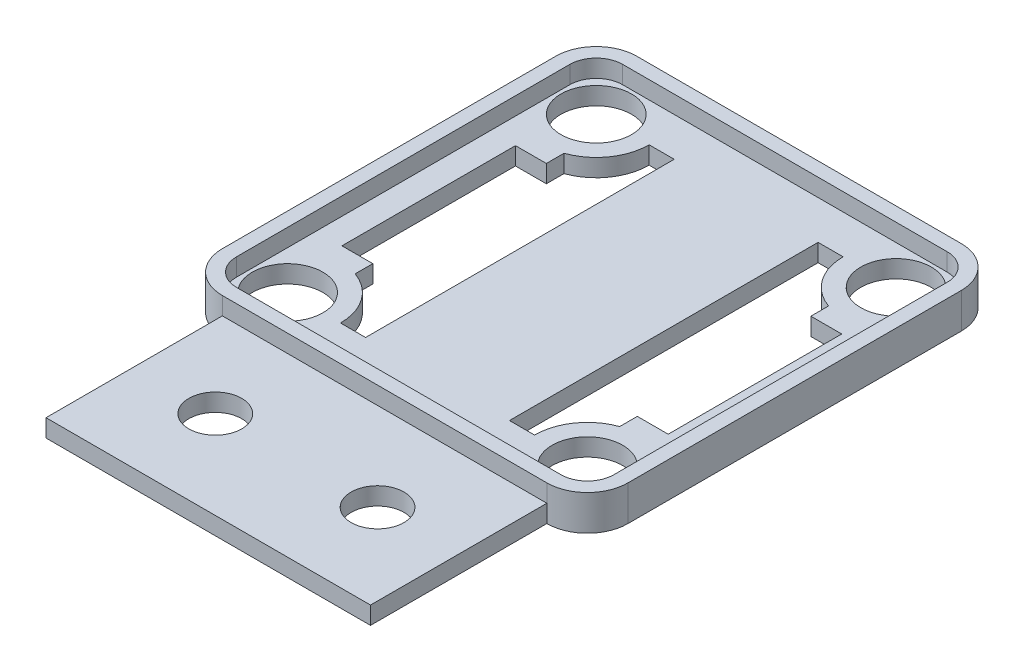
SolidWorks part; units mm, degrees
ref_plane "Front Plane" through (0, 0, 0) normal (0, 0, 1) x (1, 0, 0)
ref_plane "Top Plane" through (0, 0, 0) normal (0, 1, 0) x (1, 0, 0)
ref_plane "Right Plane" through (0, 0, 0) normal (1, 0, 0) x (0, 0, -1)
sketch "Sketch1" plane through (0, 0, 0) normal (0, 1, 0) x (1, 0, 0)
  line L1 (-12.6491, 14.6331) -> (5.7509, 14.6331)
  line L2 (-14.9491, 12.3331) -> (-14.9491, -6.5669)
  line L3 (-12.6491, -8.8669) -> (5.7509, -8.8669)
  line L4 (8.0509, 12.3331) -> (8.0509, -6.5669)
  line L5 (-14.9491, 14.6331) -> (8.0509, -8.8669) construction
  line L6 (-14.9491, -8.8669) -> (8.0509, 14.6331) construction
  arc A0 (8.0509, 12.3331) -> (5.7509, 14.6331) centre (5.7509, 12.3331) ccw
  arc A1 (-12.6491, -8.8669) -> (-14.9491, -6.5669) centre (-12.6491, -6.5669) cw
  arc A2 (5.7509, -8.8669) -> (8.0509, -6.5669) centre (5.7509, -6.5669) ccw
  arc A3 (-14.9491, 12.3331) -> (-12.6491, 14.6331) centre (-12.6491, 12.3331) cw
  point P0 (-3.4491, 2.8831)
  dimension "D3" = 2.3
  dimension "D4" = 2.3
  dimension "D1" = 23.5
  dimension "D2" = 23
extrude "Boss-Extrude1" add sketch "Sketch1" along normal blind 2
sketch "Sketch2" plane through (0, 2, 0) normal (0, 1, 0) x (1, 0, 0)
  line L8 (5.7509, 13.6331) -> (-12.6491, 13.6331)
  line L9 (-13.9491, 12.3331) -> (-13.9491, -6.5669)
  line L10 (-12.6491, -7.8669) -> (5.7509, -7.8669)
  line L11 (7.0509, -6.5669) -> (7.0509, 12.3331)
  line L12 (5.7509, 13.6331) -> (-12.6491, 13.6331)
  line L13 (-13.9491, 12.3331) -> (-13.9491, -6.5669)
  line L14 (-12.6491, -7.8669) -> (5.7509, -7.8669)
  line L15 (7.0509, -6.5669) -> (7.0509, 12.3331)
  arc A8 (7.0509, 12.3331) -> (5.7509, 13.6331) centre (5.7509, 12.3331) ccw
  arc A9 (-12.6491, 13.6331) -> (-13.9491, 12.3331) centre (-12.6491, 12.3331) ccw
  arc A10 (-13.9491, -6.5669) -> (-12.6491, -7.8669) centre (-12.6491, -6.5669) ccw
  arc A11 (5.7509, -7.8669) -> (7.0509, -6.5669) centre (5.7509, -6.5669) ccw
  arc A12 (7.0509, 12.3331) -> (5.7509, 13.6331) centre (5.7509, 12.3331) ccw
  arc A13 (-12.6491, 13.6331) -> (-13.9491, 12.3331) centre (-12.6491, 12.3331) ccw
  arc A14 (-13.9491, -6.5669) -> (-12.6491, -7.8669) centre (-12.6491, -6.5669) ccw
  arc A15 (5.7509, -7.8669) -> (7.0509, -6.5669) centre (5.7509, -6.5669) ccw
  dimension "D1" = 1
extrude "Cut-Extrude2" cut sketch "Sketch2" against normal blind 1
sketch "Sketch5" plane through (0, 1, 0) normal (0, 1, 0) x (1, 0, 0)
  line L0 (-3.4491, 13.6331) -> (-3.4491, -7.8669) construction
  line L1 (5.7509, 13.6331) -> (-12.6491, 13.6331) construction
  line L2 (-12.6491, -7.8669) -> (5.7509, -7.8669) construction
  line L3 (7.0509, 2.8831) -> (-13.9491, 2.8831) construction
  line L4 (7.0509, -6.5669) -> (7.0509, 12.3331) construction
  line L5 (-13.9491, 12.3331) -> (-13.9491, -6.5669) construction
  circle A0 centre (5.0509, 11.6331) radius 2
  circle A1 centre (5.0509, -5.8669) radius 2
  circle A2 centre (-11.9491, -5.8669) radius 2
  circle A3 centre (-11.9491, 11.6331) radius 2
  dimension "D1" = 4
extrude "Cut-Extrude3" cut sketch "Sketch5" against normal through all
sketch "Sketch6" plane through (0, 1, 0) normal (0, 1, 0) x (1, 0, 0)
  line L0 (-14.9491, 12.3331) -> (-14.9491, -6.5669) construction
  line L1 (8.0509, -6.5669) -> (8.0509, 12.3331) construction
  line L14 (4.0509, -5.8669) -> (4.0509, 11.6331)
  line L15 (4.0509, -3.0385) -> (4.0509, 8.8047)
  line L16 (2.0509, 11.6331) -> (2.0509, -5.8669)
  line L17 (-10.9491, 12.3331) -> (-10.9491, -6.5669)
  line L18 (-10.9491, 8.8047) -> (-10.9491, -3.0385)
  line L19 (-8.9491, 11.6331) -> (-8.9491, -5.8669)
  arc A5 (-11.9491, -8.8669) -> (-14.9491, -5.8669) centre (-11.9491, -5.8669) ccw
  arc A6 (-8.9491, -5.8669) -> (-10.9491, -3.0385) centre (-11.9491, -5.8669) ccw
  arc A20 (5.0509, 14.6331) -> (8.0509, 11.6331) centre (5.0509, 11.6331) ccw
  arc A21 (2.0509, 11.6331) -> (4.0509, 8.8047) centre (5.0509, 11.6331) ccw
  arc A23 (-14.9491, 11.6331) -> (-11.9491, 14.6331) centre (-11.9491, 11.6331) ccw
  arc A24 (-10.9491, 8.8047) -> (-8.9491, 11.6331) centre (-11.9491, 11.6331) ccw
  arc A26 (8.0509, -5.8669) -> (5.0509, -8.8669) centre (5.0509, -5.8669) ccw
  arc A27 (4.0509, -3.0385) -> (2.0509, -5.8669) centre (5.0509, -5.8669) ccw
  dimension "D1" = 23
  dimension "D2" = 1
  dimension "D3" = 1
  dimension "D4" = 1
  dimension "D5" = 1
  dimension "D6" = 3
  dimension "D7" = 3
extrude "Cut-Extrude4" cut sketch "Sketch6" against normal through all
sketch "Sketch7" plane through (0, 0, 8.8669) normal (0, 0, 1) x (1, 0, 0)
  line L0 (-14.9491, 2) -> (-14.9491, 0) construction
  line L1 (8.0509, 2) -> (8.0509, 0) construction
  line L2 (-12.6491, 2) -> (-12.6491, 0) construction
  line L3 (-12.6491, 1) -> (5.7509, 1)
  line L4 (5.7509, 2) -> (5.7509, 0) construction
  line L5 (5.7509, 1) -> (5.7509, 0)
  line L6 (5.7509, 0) -> (-12.6491, 0)
  line L7 (-12.6491, 0) -> (-12.6491, 1)
  dimension "D1" = 23
extrude "Boss-Extrude2" add sketch "Sketch7" along normal blind 10
sketch "Sketch8" plane through (0, 1, 0) normal (0, 1, 0) x (1, 0, 0)
  line L0 (-12.6491, -8.8669) -> (5.7509, -8.8669) construction
  line L1 (-12.6491, -18.8669) -> (-12.6491, -8.8669) construction
  line L2 (5.7509, -18.8669) -> (5.7509, -8.8669) construction
  line L3 (-3.4491, -8.8669) -> (-3.4491, -18.8669) construction
  line L4 (5.7509, -18.8669) -> (-12.6491, -18.8669) construction
  circle A0 centre (1.1509, -13.8669) radius 1.5
  circle A1 centre (-8.0491, -13.8669) radius 1.5
  dimension "D2" = 3
  dimension "D1" = 5
  dimension "D3" = 18.4
  dimension "D4" = 4.6
  dimension "D5" = 4.6
extrude "Cut-Extrude5" cut sketch "Sketch8" against normal through all
sketch "Sketch9" plane through (0, 2, 0) normal (0, 1, 0) x (1, 0, 0)
  line L8 (5.7509, 13.8331) -> (-12.6491, 13.8331)
  line L9 (-14.1491, 12.3331) -> (-14.1491, -6.5669)
  line L10 (-12.6491, -8.0669) -> (5.7509, -8.0669)
  line L11 (7.2509, -6.5669) -> (7.2509, 12.3331)
  line L12 (5.7509, 13.8331) -> (-12.6491, 13.8331)
  line L13 (-14.1491, 12.3331) -> (-14.1491, -6.5669)
  line L14 (-12.6491, -8.0669) -> (5.7509, -8.0669)
  line L15 (7.2509, -6.5669) -> (7.2509, 12.3331)
  arc A8 (7.2509, 12.3331) -> (5.7509, 13.8331) centre (5.7509, 12.3331) ccw
  arc A9 (-12.6491, 13.8331) -> (-14.1491, 12.3331) centre (-12.6491, 12.3331) ccw
  arc A10 (-14.1491, -6.5669) -> (-12.6491, -8.0669) centre (-12.6491, -6.5669) ccw
  arc A11 (5.7509, -8.0669) -> (7.2509, -6.5669) centre (5.7509, -6.5669) ccw
  arc A12 (7.2509, 12.3331) -> (5.7509, 13.8331) centre (5.7509, 12.3331) ccw
  arc A13 (-12.6491, 13.8331) -> (-14.1491, 12.3331) centre (-12.6491, 12.3331) ccw
  arc A14 (-14.1491, -6.5669) -> (-12.6491, -8.0669) centre (-12.6491, -6.5669) ccw
  arc A15 (5.7509, -8.0669) -> (7.2509, -6.5669) centre (5.7509, -6.5669) ccw
  dimension "D1" = 0.8
extrude "Cut-Extrude6" cut sketch "Sketch9" against normal blind 1
sketch "Sketch11" plane through (0, 1, 0) normal (0, 1, 0) x (1, 0, 0)
  line L0 (-8.9491, 11.6331) -> (-7.528, 11.6331)
  line L1 (-7.528, 11.6331) -> (-7.528, -5.8669)
  line L2 (-7.528, -5.8669) -> (-8.9491, -5.8669)
  line L3 (-8.9491, -5.8669) -> (-8.9491, 11.6331)
  line L4 (-3.4491, 13.8331) -> (-3.4491, -8.0669) construction
  line L5 (5.7509, 13.8331) -> (-12.6491, 13.8331) construction
  line L6 (-12.6491, -8.0669) -> (5.7509, -8.0669) construction
  line L7 (0.6299, -5.8669) -> (2.0509, -5.8669)
  line L8 (0.6299, 11.6331) -> (0.6299, -5.8669)
  line L9 (2.0509, 11.6331) -> (0.6299, 11.6331)
  line L10 (2.0509, -5.8669) -> (2.0509, 11.6331)
  line L11 (-10.9491, 8.8047) -> (-10.9491, -3.0385) construction
  line L12 (-12.6991, 7.8031) -> (-10.9491, 7.8031)
  line L13 (-12.6991, 7.8031) -> (-12.6991, -2.0369)
  line L14 (-12.6991, -2.0369) -> (-10.9491, -2.0369)
  line L15 (-10.9491, 7.8031) -> (-10.9491, -2.0369)
  line L16 (5.8009, -2.0369) -> (4.0509, -2.0369)
  line L17 (4.0509, 7.8031) -> (4.0509, -2.0369)
  line L18 (5.8009, 7.8031) -> (4.0509, 7.8031)
  line L19 (5.8009, 7.8031) -> (5.8009, -2.0369)
  point P22 (-10.9491, 2.8831)
  point P23 (-10.9491, 2.8831)
  dimension "D1" = 9.84
  dimension "D2" = 1.75
extrude "Cut-Extrude7" cut sketch "Sketch11" against normal through all
